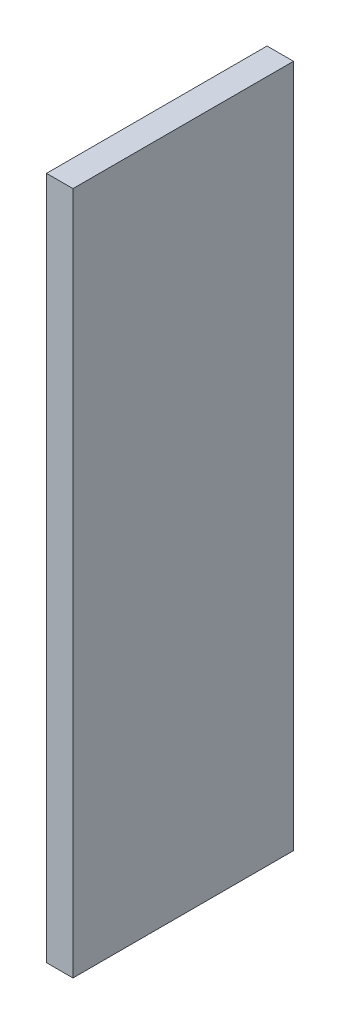
SolidWorks part; units mm, degrees
ref_plane "Front Plane" through (0, 0, 0) normal (1, 0, 0) x (0, 1, 0)
ref_plane "Top Plane" through (0, 0, 0) normal (0, 0, 1) x (0, 1, 0)
ref_plane "Right Plane" through (0, 0, 0) normal (0, 1, 0) x (-1, 0, 0)
sketch "Sketch1" plane through (0, 0, 0) normal (1, 0, 0) x (0, 1, 0)
  line L1 (0, 0) -> (155, 0)
  line L2 (0, 0) -> (0, 50)
  line L3 (0, 50) -> (155, 50)
  line L4 (155, 0) -> (155, 50)
  dimension "D1" = 155
  dimension "D2" = 50
extrude "Boss-Extrude1" add sketch "Sketch1" along normal blind 6
